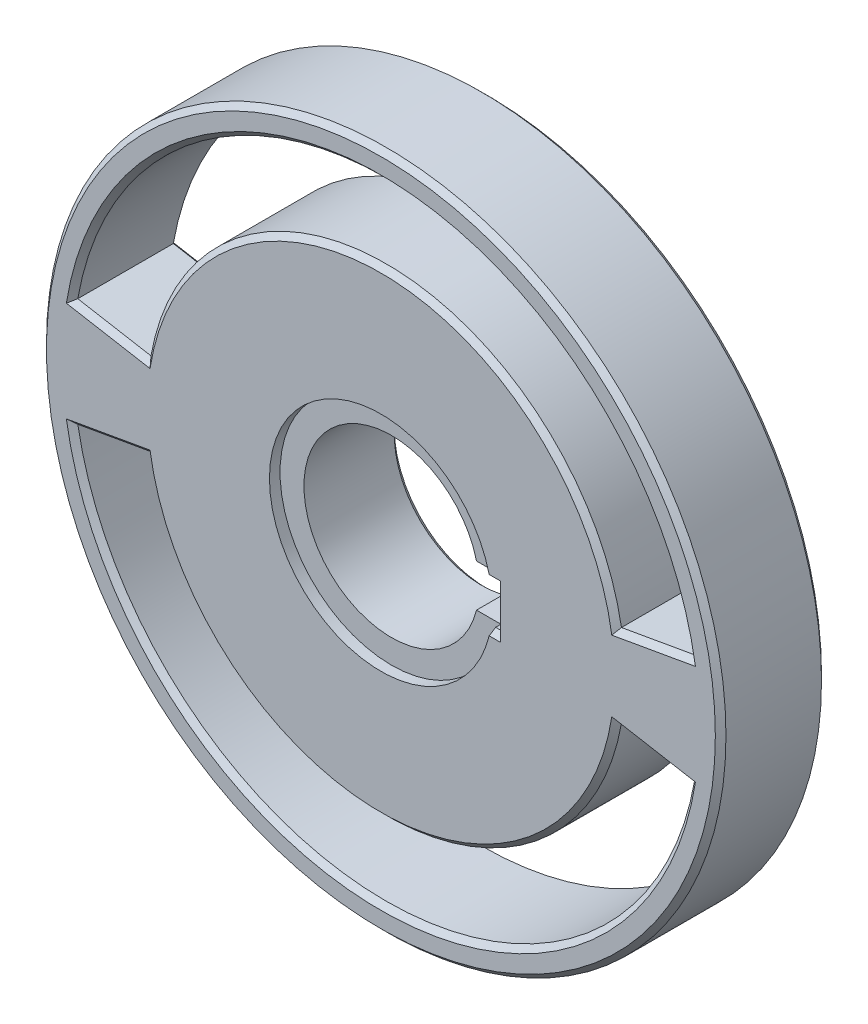
SolidWorks part; units mm, degrees
ref_plane "前视基准面" through (0, 0, 0) normal (0, 0, 1) x (1, 0, 0)
ref_plane "上视基准面" through (0, 0, 0) normal (0, 1, 0) x (1, 0, 0)
ref_plane "右视基准面" through (0, 0, 0) normal (1, 0, 0) x (0, 0, -1)
other "Configuration Table"
sketch "草图1" plane through (0, 0, 0) normal (0, 0, 1) x (1, 0, 0)
  circle A0 centre (0, 0) radius 32
extrude "凸台-拉伸1" add sketch "草图1" along normal blind 10
sketch "草图2" plane through (0, 0, 0) normal (0, 0, 1) x (1, 0, 0)
  circle A0 centre (0, 0) radius 8.25
extrude "切除-拉伸1" cut sketch "草图2" along normal blind 10
sketch "草图4" plane through (0, 0, 0) normal (0, 0, 1) x (1, 0, 0)
  line L1 (8.0037, -2.0009) -> (10.75, -2.0009)
  line L2 (8.0037, -2.0009) -> (8.0037, 2)
  line L3 (8.0037, 2) -> (10.75, 2)
  line L4 (10.75, -2.0009) -> (10.75, 2)
  circle A0 centre (0, 0) radius 8.25 construction
extrude "切除-拉伸3" cut sketch "草图4" along normal blind 10
sketch "草图5" plane through (0, 0, 0) normal (0, 0, 1) x (1, 0, 0)
  line L0 (-22.1582, 3.9071) -> (-29.0518, 5.1226)
  line L1 (29.0518, 5.1226) -> (22.1582, 3.9071)
  arc A0 (22.1582, 3.9071) -> (-22.1582, 3.9071) centre (0, 0) ccw
  arc A1 (-29.0518, 5.1226) -> (29.0518, 5.1226) centre (0, 0) cw
extrude "切除-拉伸4" cut sketch "草图5" along normal blind 10
sketch "草图6" plane through (0, 0, 0) normal (0, 0, 1) x (1, 0, 0)
  line L0 (22.1582, -3.9071) -> (29.0518, -5.1226)
  line L1 (-29.0518, -5.1226) -> (-22.1582, -3.9071)
  arc A0 (-22.1582, -3.9071) -> (22.1582, -3.9071) centre (0, 0) ccw
  arc A1 (29.0518, -5.1226) -> (-29.0518, -5.1226) centre (0, 0) cw
extrude "切除-拉伸5" cut sketch "草图6" along normal blind 10
chamfer "倒角1" distance 0.5 angle 45 13 edges at (0, -29.5, 10) (25.605, -4.5149, 10) (0, -22.5, 10) (-25.605, -4.5149, 10) (0, 29.5, 10) (-25.605, 4.5149, 10) (0, 22.5, 10) (25.605, 4.5149, 10) (9.377, 2, 10) (-8.25, 0.0005, 10) (9.3768, -2.0009, 10) (10.75, -0.0005, 10) (32, 0, 10)
chamfer "倒角2" distance 0.5 angle 45 13 edges at (25.605, -4.5148, 0) (0, -29.5, 0) (-25.605, -4.5149, 0) (0, -22.5, 0) (-8.25, 0.0005, 0) (9.377, 2, 0) (10.75, -0.0005, 0) (9.3768, -2.0009, 0) (32, 0, 0) (-25.605, 4.5149, 0) (0, 29.5, 0) (25.605, 4.5149, 0) (0, 22.5, 0)
sketch "草图7" plane through (0, 0, 10) normal (0, 0, 1) x (1, 0, 0)
  circle A0 centre (0, 0) radius 10.5
extrude "切除-拉伸6" cut sketch "草图7" against normal blind 1
